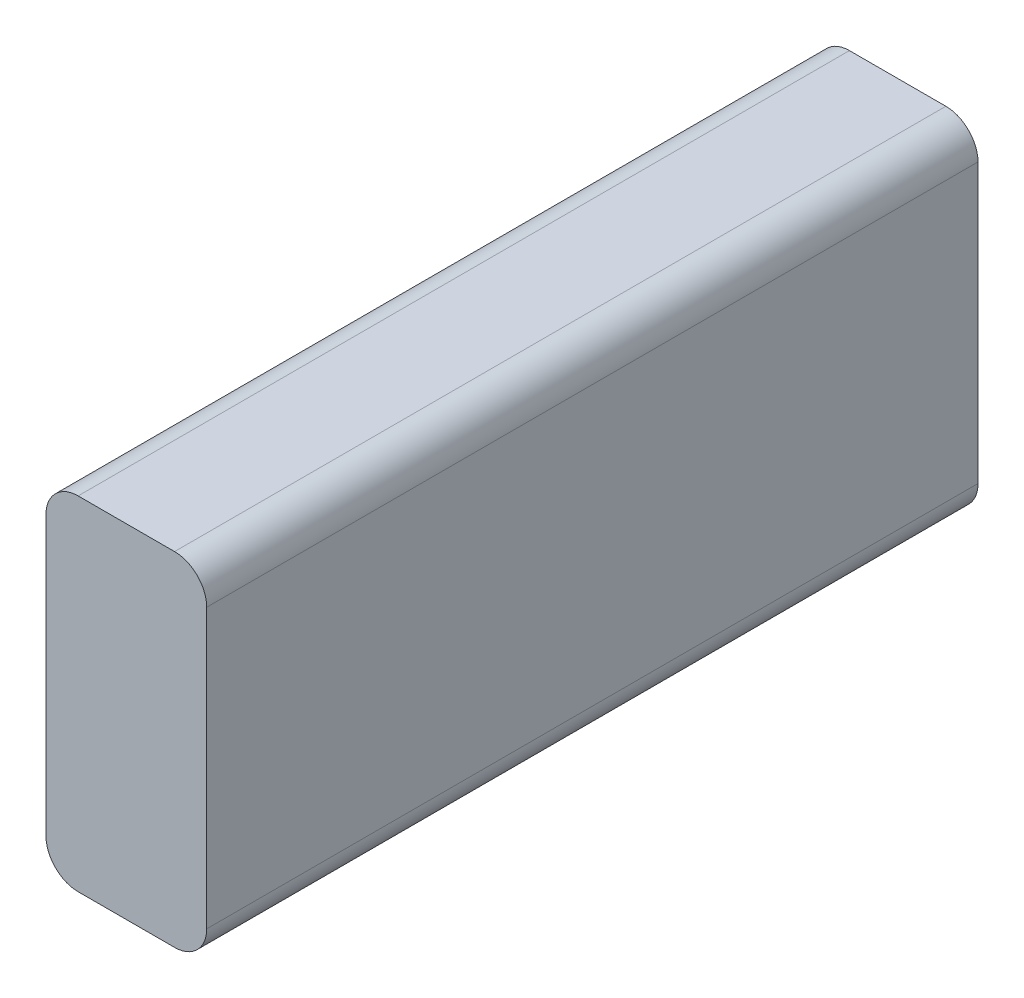
SolidWorks part; units mm, degrees
ref_plane "Front Plane" through (0, 0, 0) normal (0, 0, 1) x (1, 0, 0)
ref_plane "Top Plane" through (0, 0, 0) normal (0, 1, 0) x (1, 0, 0)
ref_plane "Right Plane" through (0, 0, 0) normal (1, 0, 0) x (0, 0, -1)
sketch "Sketch1" plane through (0, 0, 0) normal (0, 0, 1) x (1, 0, 0)
  line L1 (190.5, -406.4) -> (-190.5, -406.4)
  line L2 (190.5, -406.4) -> (190.5, 406.4)
  line L3 (190.5, 406.4) -> (-190.5, 406.4)
  line L4 (-190.5, -406.4) -> (-190.5, 406.4)
  line L5 (190.5, -406.4) -> (-190.5, 406.4) construction
  line L6 (190.5, 406.4) -> (-190.5, -406.4) construction
  point P0 (0, 0)
  dimension "D1" = 812.8
  dimension "D2" = 381
extrude "Boss-Extrude1" add sketch "Sketch1" along normal blind 1828.8
fillet "Fillet1" radius 76.2 4 edges at (190.5, -406.4, 914.4) (-190.5, -406.4, 914.4) (-190.5, 406.4, 914.4) (190.5, 406.4, 914.4)
